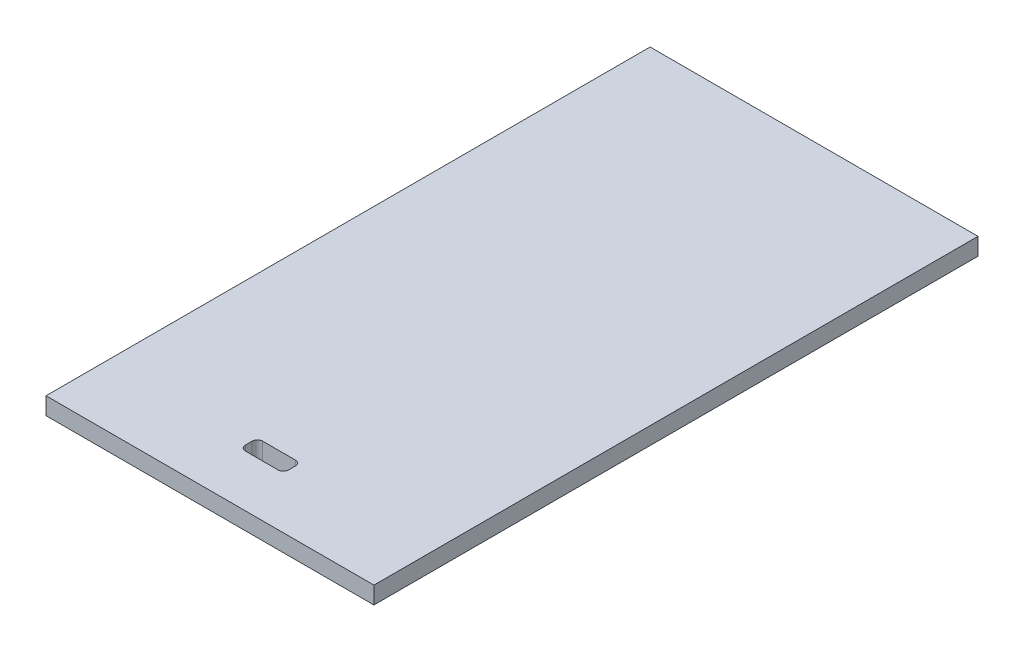
SolidWorks part; units mm, degrees
ref_plane "前视基准面" through (0, 0, 0) normal (0, 0, 1) x (1, 0, 0)
ref_plane "上视基准面" through (0, 0, 0) normal (0, 1, 0) x (1, 0, 0)
ref_plane "右视基准面" through (0, 0, 0) normal (1, 0, 0) x (0, 0, -1)
other "Configuration Table"
sketch "草图1" plane through (0, 0, 0) normal (0, 1, 0) x (1, 0, 0)
  line L1 (0, 0) -> (380, 0)
  line L2 (0, 0) -> (0, 700)
  line L3 (0, 700) -> (380, 700)
  line L4 (380, 230) -> (380, 700)
  line L5 (380, 0) -> (716, 0)
  line L7 (380, 230) -> (716, 230)
  line L8 (716, 0) -> (716, 230)
  dimension "D1" = 380
  dimension "D2" = 700
  dimension "D3" = 336
  dimension "D4" = 230
extrude "凸台-拉伸1" add sketch "草图1" along normal blind 20
sketch "草图2" plane through (0, 20, 0) normal (0, 1, 0) x (1, 0, 0)
  line L1 (380, 230) -> (716, 230)
  line L2 (380, 230) -> (380, 0)
  line L3 (380, 0) -> (716, 0)
  line L4 (716, 230) -> (716, 0)
extrude "切除-拉伸1" cut sketch "草图2" against normal blind 20
sketch "草图3" plane through (0, 20, 0) normal (0, 1, 0) x (1, 0, 0)
  line L0 (0, 0) -> (380, 0) construction
  line L1 (171, 80) -> (209, 80)
  line L2 (165, 74) -> (165, 66)
  line L3 (171, 60) -> (209, 60)
  line L4 (215, 74) -> (215, 66)
  arc A0 (209, 60) -> (215, 66) centre (209, 66) ccw
  arc A1 (209, 80) -> (215, 74) centre (209, 74) cw
  arc A2 (171, 80) -> (165, 74) centre (171, 74) ccw
  arc A3 (165, 66) -> (171, 60) centre (171, 66) ccw
  point P6 (215, 60)
  point P9 (215, 80)
  point P12 (165, 80)
  point P15 (190, 60)
  point P18 (190, 0)
  dimension "D3" = 6
  dimension "D1" = 20
  dimension "D2" = 50
  dimension "D4" = 0
  dimension "D5" = 60
extrude "切除-拉伸2" cut sketch "草图3" against normal blind 20
